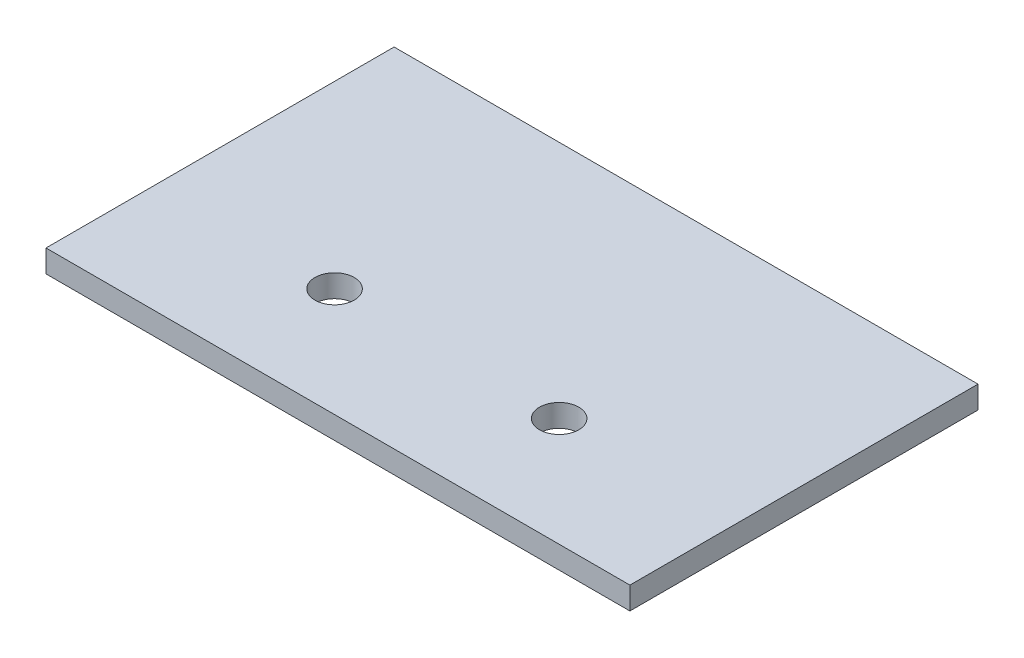
SolidWorks part; units mm, degrees
ref_plane "Alzado" through (0, 0, 0) normal (0, 0, 1) x (1, 0, 0)
ref_plane "Planta" through (0, 0, 0) normal (0, 1, 0) x (1, 0, 0)
ref_plane "Vista lateral" through (0, 0, 0) normal (1, 0, 0) x (0, 0, -1)
sketch "Sketch1" plane through (0, 0, 0) normal (0, 1, 0) x (1, 0, 0)
  line L1 (-26, 15.5) -> (26, 15.5)
  line L2 (-26, 15.5) -> (-26, -15.5)
  line L3 (-26, -15.5) -> (26, -15.5)
  line L4 (26, 15.5) -> (26, -15.5)
  line L5 (-26, 15.5) -> (26, -15.5) construction
  line L6 (-26, -15.5) -> (26, 15.5) construction
  circle A0 centre (-10, -5.8) radius 1.75
  circle A1 centre (10, -5.8) radius 1.75
  point P0 (0, 0)
  dimension "D6" = 3.5
  dimension "D7" = 3.5
  dimension "D1" = 52
  dimension "D2" = 31
  dimension "D3" = 21.3
  dimension "D4" = 20
  dimension "D5" = 10
extrude "Boss-Extrude1" add sketch "Sketch1" along normal blind 2
